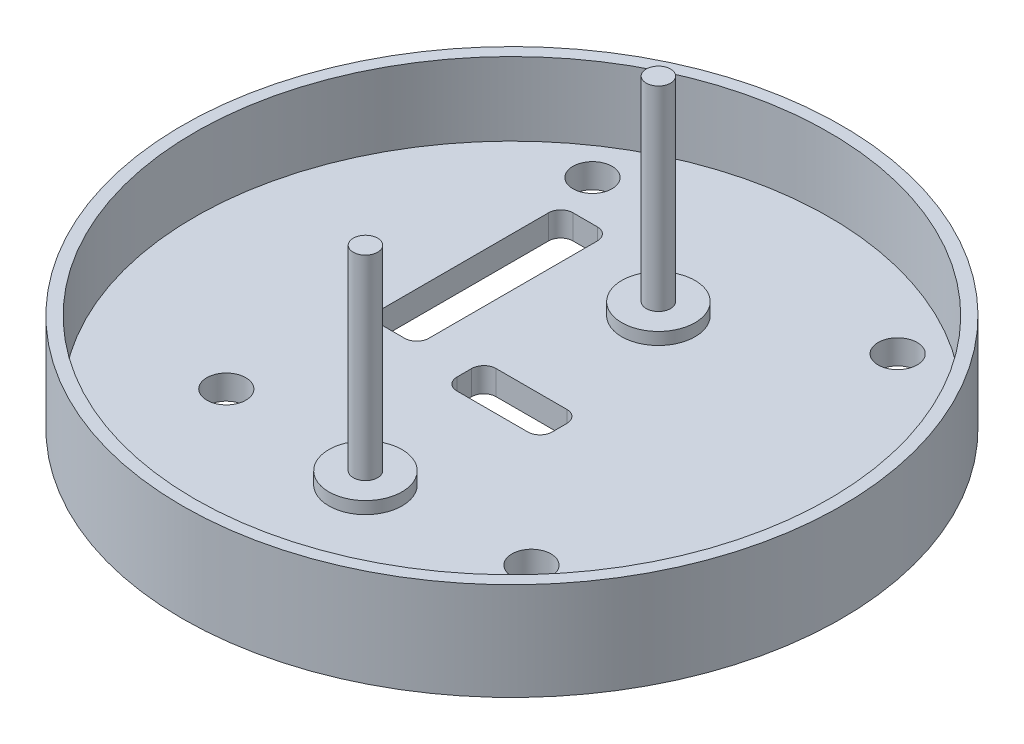
SolidWorks part; units mm, degrees
ref_plane "Front Plane" through (0, 0, 0) normal (0, 0, 1) x (1, 0, 0)
ref_plane "Top Plane" through (0, 0, 0) normal (0, 1, 0) x (1, 0, 0)
ref_plane "Right Plane" through (0, 0, 0) normal (1, 0, 0) x (0, 0, -1)
sketch "Sketch1" plane through (0, 0, 0) normal (0, 1, 0) x (1, 0, 0)
  circle A0 centre (0, 0) radius 34.29
  dimension "D1" = 68.58
extrude "Boss-Extrude1" add sketch "Sketch1" along normal blind 10.16
sketch "Sketch2" plane through (0, 10.16, 0) normal (0, 1, 0) x (1, 0, 0)
  circle A0 centre (0, 0) radius 33.02
  circle A1 centre (0, 0) radius 34.29 construction
  dimension "D1" = 66.04
extrude "Cut-Extrude1" cut sketch "Sketch2" against normal blind 7.62
sketch "Sketch3" plane through (0, 2.54, 0) normal (0, 1, 0) x (1, 0, 0)
  line L0 (0, -15.24) -> (0, 15.24) construction
  line L2 (0, -5.588) -> (0, 5.588) construction
  circle A0 centre (0, -15.24) radius 3.81
  circle A1 centre (0, 15.24) radius 3.81
  dimension "D2" = 7.62
  dimension "D3" = 7.62
  dimension "D1" = 30.48
extrude "Boss-Extrude2" add sketch "Sketch3" along normal blind 1.27
sketch "Sketch4" plane through (0, 3.81, 0) normal (0, 1, 0) x (1, 0, 0)
  circle A0 centre (0, -15.24) radius 1.27
  circle A1 centre (0, 15.24) radius 1.27
  circle A2 centre (0, -15.24) radius 3.81 construction
  circle A4 centre (0, 15.24) radius 3.81 construction
  dimension "D1" = 2.54
  dimension "D2" = 2.54
extrude "Boss-Extrude3" add sketch "Sketch4" along normal blind 20.32
sketch "Sketch8" plane through (0, 2.54, 0) normal (0, 1, 0) x (1, 0, 0)
  line L0 (0, -15.24) -> (0, 15.24) construction
  line L2 (3.683, 2.032) -> (-3.683, 2.032)
  line L3 (4.953, 0.762) -> (4.953, -0.762)
  line L4 (3.683, -2.032) -> (-3.683, -2.032)
  line L5 (-4.953, 0.762) -> (-4.953, -0.762)
  line L6 (4.953, 2.032) -> (-4.953, -2.032) construction
  line L7 (4.953, -2.032) -> (-4.953, 2.032) construction
  arc A0 (-3.683, -2.032) -> (-4.953, -0.762) centre (-3.683, -0.762) cw
  arc A1 (-3.683, 2.032) -> (-4.953, 0.762) centre (-3.683, 0.762) ccw
  arc A2 (4.953, -0.762) -> (3.683, -2.032) centre (3.683, -0.762) cw
  arc A3 (3.683, 2.032) -> (4.953, 0.762) centre (3.683, 0.762) cw
  point P4 (0, 0)
  point P9 (0, -2.032)
  dimension "D3" = 1.27
  dimension "D1" = 9.906
  dimension "D2" = 4.064
extrude "Cut-Extrude3" cut sketch "Sketch8" against normal up to next
sketch "Sketch9" plane through (0, 2.54, 0) normal (0, 1, 0) x (1, 0, 0)
  line L1 (-13.716, 0) -> (-11.176, 0)
  line L2 (-14.986, 1.27) -> (-14.986, 18.796)
  line L3 (-13.716, 20.066) -> (-11.176, 20.066)
  line L4 (-9.906, 1.27) -> (-9.906, 18.796)
  line L5 (-14.986, 0) -> (-9.906, 20.066) construction
  line L6 (-14.986, 20.066) -> (-9.906, 0) construction
  line L9 (4.953, 0) -> (-22.7571, 0) construction
  line L10 (4.953, -0.762) -> (4.953, 0.762) construction
  line L11 (3.683, 2.032) -> (-3.683, 2.032) construction
  arc A0 (-11.176, 20.066) -> (-9.906, 18.796) centre (-11.176, 18.796) cw
  arc A1 (-14.986, 18.796) -> (-13.716, 20.066) centre (-13.716, 18.796) cw
  arc A2 (-13.716, 0) -> (-14.986, 1.27) centre (-13.716, 1.27) cw
  arc A3 (-11.176, 0) -> (-9.906, 1.27) centre (-11.176, 1.27) ccw
  point P11 (0, 2.032)
  dimension "D4" = 1.27
  dimension "D1" = 20.066
  dimension "D2" = 5.08
  dimension "D3" = 9.906
extrude "Cut-Extrude4" cut sketch "Sketch9" against normal up to next
sketch "Sketch11" plane through (0, 0, 0) normal (0, -1, 0) x (1, 0, 0)
  line L0 (-3.683, -2.032) -> (3.683, -2.032) construction
  line L1 (-15.875, 13.843) -> (15.875, 13.843) construction
  line L2 (-15.875, 13.843) -> (-15.875, -24.257) construction
  line L3 (-15.875, -24.257) -> (15.875, -24.257) construction
  line L4 (15.875, 13.843) -> (15.875, -24.257) construction
  line L5 (-15.875, 13.843) -> (15.875, -24.257) construction
  line L6 (-15.875, -24.257) -> (15.875, 13.843) construction
  line L7 (-14.986, -1.27) -> (-14.986, -18.796) construction
  circle A0 centre (15.875, 13.843) radius 2.032
  circle A1 centre (-15.875, 13.843) radius 2.032
  circle A2 centre (-15.875, -24.257) radius 2.032
  circle A3 centre (15.875, -24.257) radius 2.032
  point P0 (0, -5.207)
  dimension "D3" = 4.064
  dimension "D4" = 4.064
  dimension "D5" = 4.064
  dimension "D6" = 4.064
  dimension "D1" = 38.1
  dimension "D2" = 31.75
  dimension "D7" = 3.175
extrude "Cut-Extrude5" cut sketch "Sketch11" against normal up to next
